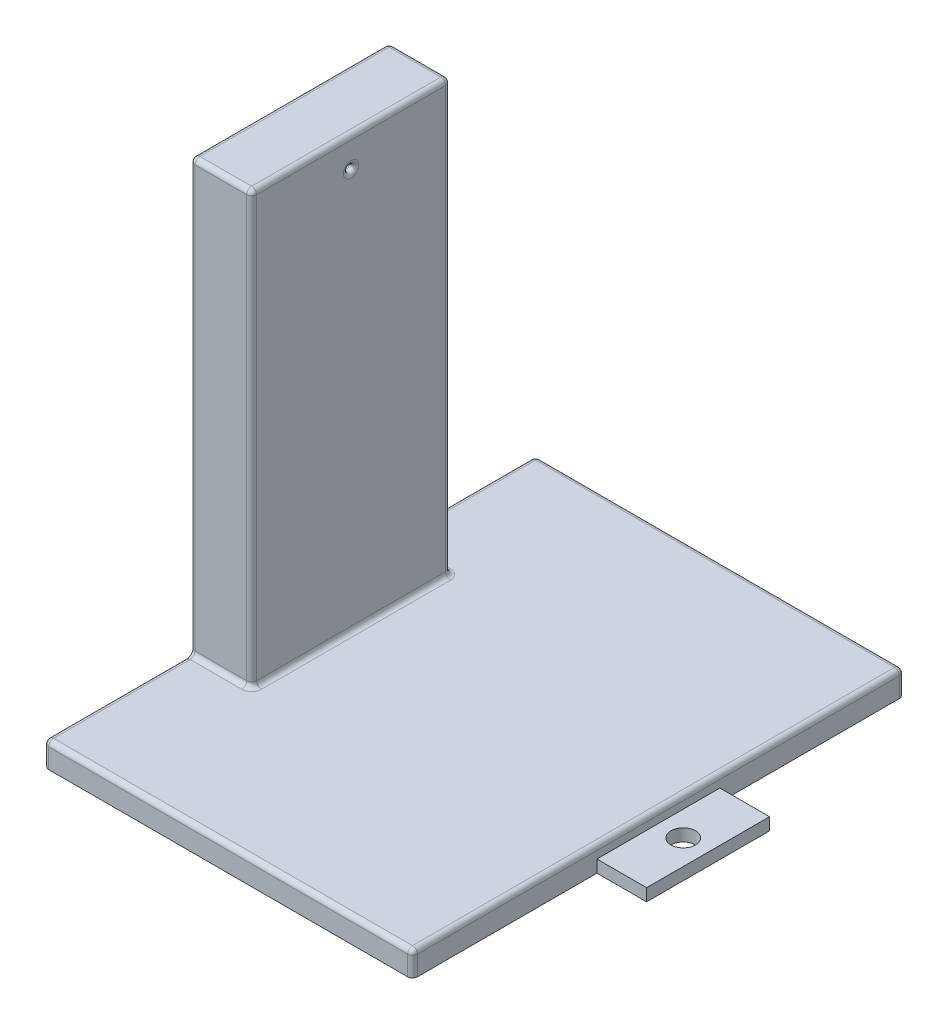
SolidWorks part; units mm, degrees
ref_plane "Plan de face" through (0, 0, 0) normal (0, 0, 1) x (1, 0, 0)
ref_plane "Plan de dessus" through (0, 0, 0) normal (0, 1, 0) x (1, 0, 0)
ref_plane "Plan de droite" through (0, 0, 0) normal (1, 0, 0) x (0, 0, -1)
sketch "Esquisse2" plane through (0, 0, 0) normal (0, 1, 0) x (1, 0, 0)
  line L0 (75, 100) -> (-75, 100)
  line L1 (75, -100) -> (75, 100)
  line L2 (-75, -100) -> (75, -100)
  line L3 (-75, 100) -> (-75, -100)
extrude "Boss.-Extru.2" add sketch "Esquisse2" along normal blind 10
sketch "Esquisse3" plane through (0, 0, 0) normal (0, 1, 0) x (1, 0, 0)
  line L0 (-75, 40.4491) -> (-75, -40.4491)
  line L1 (-75, -40.4491) -> (-50, -40.4491)
  line L2 (-50, -40.4491) -> (-50, 40.4491)
  line L3 (-50, 40.4491) -> (-75, 40.4491)
extrude "Boss.-Extru.3" add sketch "Esquisse3" along normal blind 165
sketch "Esquisse7" plane through (0, 0, 0) normal (1, 0, 0) x (0, 0, -1)
  line L0 (-100, 0) -> (100, 0) construction
  line L1 (-25, 5) -> (-25, 0)
  line L2 (25, 5) -> (-25, 5)
  line L3 (25, 0) -> (25, 5)
  line L4 (-25, 0) -> (25, 0)
  point P8 (0, 0)
extrude "Boss.-Extru.4" add sketch "Esquisse7" along normal blind 95.2
sketch "Esquisse8" plane through (0, 0, 0) normal (0, 1, 0) x (1, 0, 0)
  circle A0 centre (85.1, 0) radius 5
extrude "Enlèv. mat.-Extru.2" cut sketch "Esquisse8" against normal blind 95.2 and the other way blind 95.2
sketch "Esquisse9" plane through (0, 0, 0) normal (0, 1, 0) x (1, 0, 0)
  line L4 (-50, 40.4491) -> (-75, 40.4491)
  line L5 (-75, 40.4491) -> (-75, -40.4491)
  line L6 (-75, -40.4491) -> (-50, -40.4491)
  line L7 (-50, -40.4491) -> (-50, 40.4491)
  line L8 (-50, 40.4491) -> (-75, 40.4491)
  line L9 (-75, 40.4491) -> (-75, -40.4491)
  line L10 (-75, -40.4491) -> (-50, -40.4491)
  line L11 (-50, -40.4491) -> (-50, 40.4491)
  dimension "D1" = 0
extrude "Boss.-Extru.5" add sketch "Esquisse9" along normal blind 185.2
sketch "Esquisse10" plane through (0, 0, 0) normal (1, 0, 0) x (0, 0, -1)
  line L1 (0, 185.2) -> (0, 172.95) construction
  line L2 (-40.4491, 185.2) -> (40.4491, 185.2) construction
  circle A0 centre (0, 172.95) radius 1.125
  dimension "D2" = 2.25
  dimension "D1" = 12.25
extrude "Enlèv. mat.-Extru.3" cut sketch "Esquisse10" against normal blind 185.2
fillet "Congé1" radius 2 23 edges at (0, 10, -100) (75, 10, 0) (0, 10, 100) (-75, 10, 70.2246) (-75, 5, 100) (-75, 0, 0) (-75, 5, -100) (-75, 10, -70.2246) (-75, 172.95, -1.125) (-50, 10, 0) (-50, 172.95, 1.125) (-75, 185.2, 0) (-50, 185.2, 0) (-50, 97.6, -40.4491) (-62.5, 185.2, -40.4491) (-75, 97.6, -40.4491) (-62.5, 10, -40.4491) (-75, 97.6, 40.4491) (-62.5, 185.2, 40.4491) (-50, 97.6, 40.4491) (-62.5, 10, 40.4491) (75, 5, 100) (75, 5, -100)
